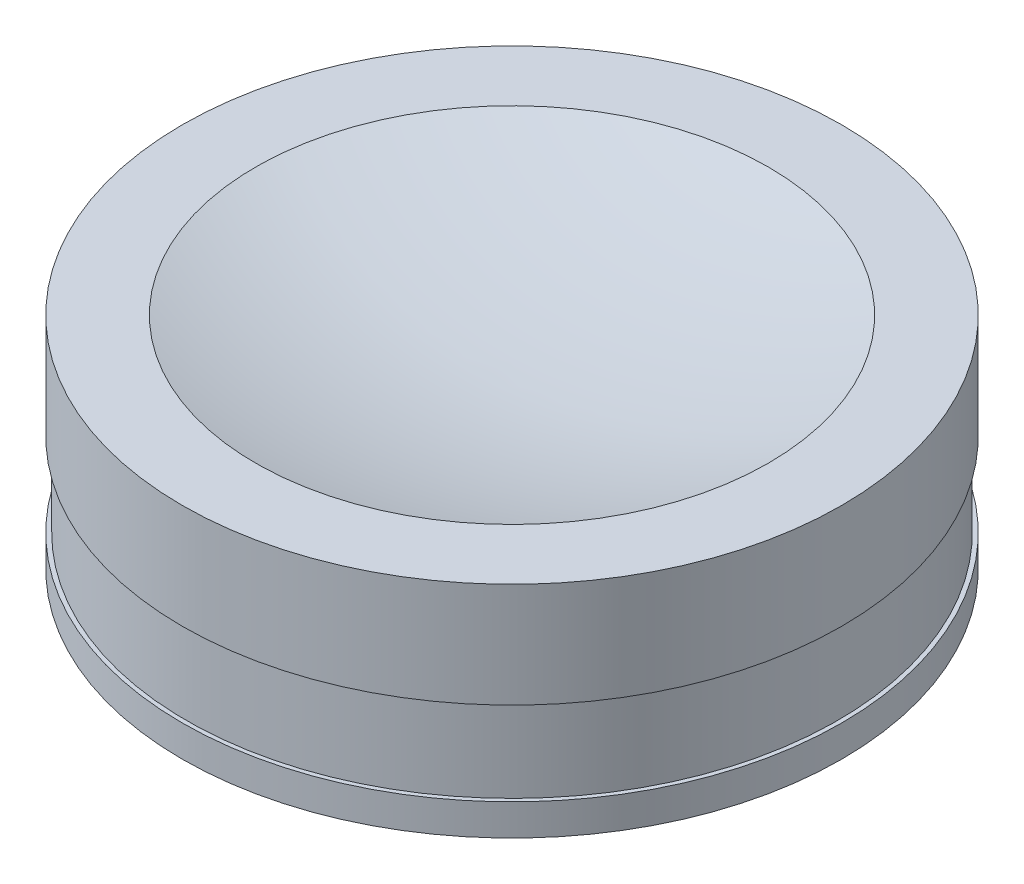
SolidWorks part; units mm, degrees
ref_plane "Front Plane" through (0, 0, 0) normal (0, 0, 1) x (1, 0, 0)
ref_plane "Top Plane" through (0, 0, 0) normal (0, 1, 0) x (1, 0, 0)
ref_plane "Right Plane" through (0, 0, 0) normal (1, 0, 0) x (0, 0, -1)
sketch "Sketch1" plane through (0, 0, 0) normal (0, 0, 1) x (1, 0, 0)
  line L0 (0, 0) -> (0, 11.5442) construction
  line L1 (0, 29.4) -> (0, 34.4)
  line L2 (49, 42) -> (63, 42)
  line L3 (63, 42) -> (63, 22)
  line L4 (63, 22) -> (62.2, 22)
  line L5 (62.2, 22) -> (62.2, 6)
  line L6 (62.2, 6) -> (63, 6)
  line L7 (63, 6) -> (63, 0)
  line L8 (63, 0) -> (58, 0)
  line L9 (58, 0) -> (58, 6.5)
  line L10 (58, 9.5) -> (58, 12.5)
  line L11 (58, 15.5) -> (58, 37)
  line L12 (58, 37) -> (49, 37)
  line L13 (49, 37) -> (49, 42) construction
  line L14 (18.6838, 34.4) -> (6.4684, 34.4) construction
  line L15 (18.6838, 29.4) -> (6.4684, 29.4) construction
  arc A0 (0, 34.4) -> (49, 42) centre (0, 196.1605) ccw
  arc A1 (0, 29.4) -> (49, 37) centre (0, 191.1605) ccw
  arc A2 (58, 12.5) -> (58, 15.5) centre (58, 14) cw
  arc A3 (58, 6.5) -> (58, 9.5) centre (58, 8) cw
  dimension "D8" = 1.5
  dimension "D1" = 126
  dimension "D2" = 14
  dimension "D3" = 42
  dimension "D4" = 20
  dimension "D5" = 6
  dimension "D6" = 0.8
  dimension "D7" = 5
  dimension "D9" = 6.5
  dimension "D10" = 3
  dimension "D11" = 7.6
revolve "Revolve1" add sketch "Sketch1" angle 360 about L0
